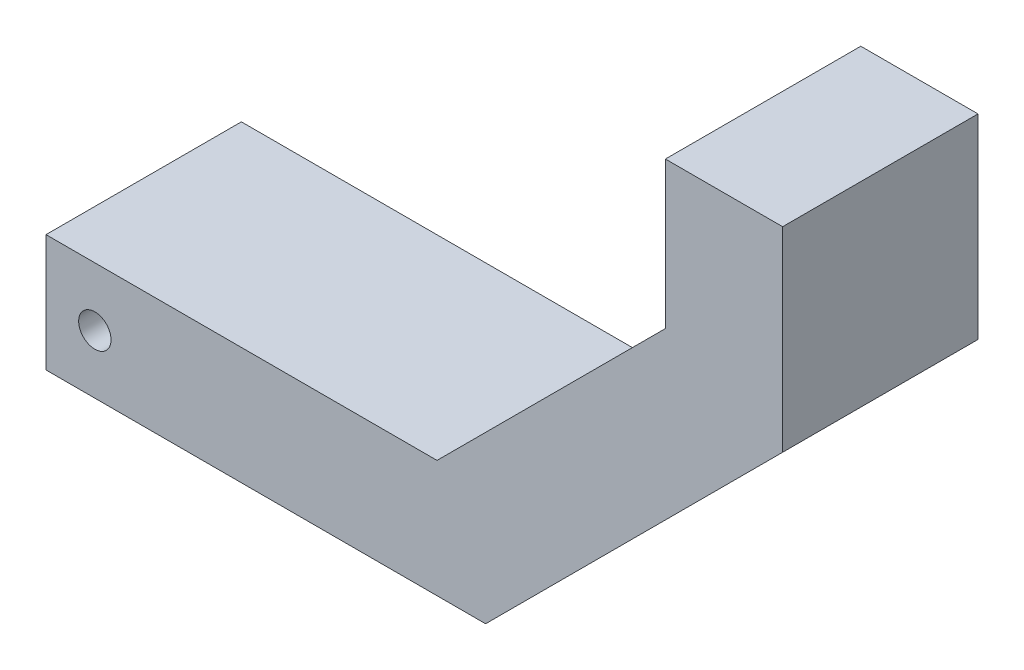
SolidWorks part; units mm, degrees
ref_plane "Front Plane" through (0, 0, 0) normal (0, 0, 1) x (1, 0, 0)
ref_plane "Top Plane" through (0, 0, 0) normal (0, 1, 0) x (1, 0, 0)
ref_plane "Right Plane" through (0, 0, 0) normal (1, 0, 0) x (0, 0, -1)
sketch "Sketch1" plane through (0, 0, 0) normal (0, 0, 1) x (1, 0, 0)
  line L0 (0, 0) -> (45, 0)
  line L1 (45, 0) -> (75.4056, 30.4056)
  line L2 (75.4056, 30.4056) -> (75.4056, 50.4056)
  line L3 (0, 12) -> (40.0294, 12)
  line L4 (40.0294, 12) -> (63.4056, 35.3762)
  line L5 (63.4056, 35.3762) -> (63.4056, 50.4056)
  line L6 (0, 12) -> (0, 0)
  line L7 (63.4056, 50.4056) -> (75.4056, 50.4056)
  circle A0 centre (5, 6) radius 1.6579
  dimension "D1" = 135
  dimension "D2" = 135
  dimension "D3" = 12
extrude "Boss-Extrude1" add sketch "Sketch1" along normal blind 20
